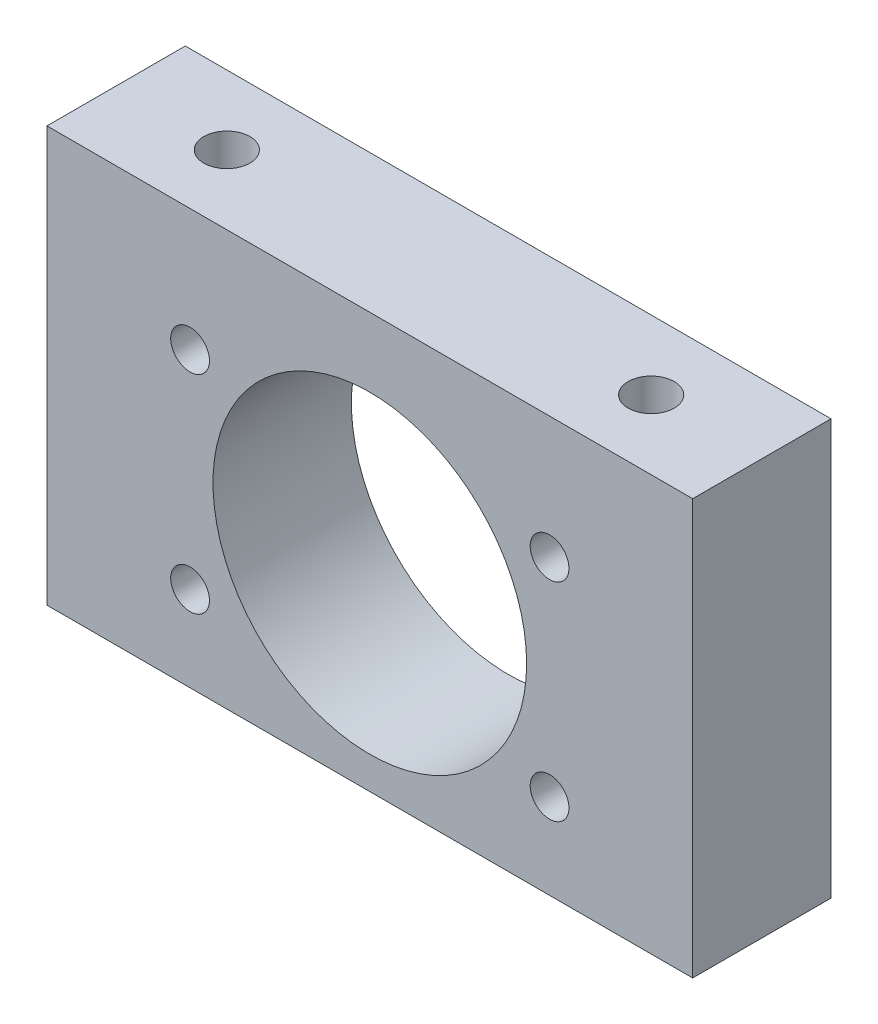
SolidWorks part; units mm, degrees
material "SKD11淬火HRC56-60"
ref_plane "前基準面" through (0, 0, 0) normal (0, 0, 1) x (1, 0, 0)
ref_plane "上基準面" through (0, 0, 0) normal (0, 1, 0) x (1, 0, 0)
ref_plane "右基準面" through (0, 0, 0) normal (1, 0, 0) x (0, 0, -1)
sketch "草图1" plane through (0, 0, 0) normal (0, 0, 1) x (1, 0, 0)
  line L1 (0, 0) -> (70, 0)
  line L2 (0, 0) -> (0, 45)
  line L3 (0, 45) -> (70, 45)
  line L4 (70, 0) -> (70, 45)
  dimension "D1" = 70
  dimension "D2" = 45
extrude "凸台-拉伸1" add sketch "草图1" along normal blind 15
sketch "草图2" plane through (0, 0, 15) normal (0, 0, 1) x (1, 0, 0)
  line L0 (35, 45) -> (35, 5.7798) construction
  line L1 (70, 45) -> (0, 45) construction
  circle A0 centre (35, 20.5) radius 17
  dimension "D1" = 34
  dimension "D2" = 24.5
extrude "切除-拉伸1" cut sketch "草图2" against normal through all
hole_wizard "M6 螺纹孔1" positions "草图4" profile "草图3" tap size "M6" standard "ISO"
sketch "草图4" plane through (0, 45, 0) normal (0, 1, 0) x (-1, 0, 0)
  line L0 (0, 7.5) -> (-70, 7.5) construction
  line L1 (0, 15) -> (0, 0) construction
  line L2 (-70, 15) -> (-70, 0) construction
  line L3 (-35, 0) -> (-35, 15) construction
  line L4 (-70, 0) -> (0, 0) construction
  line L5 (-70, 15) -> (0, 15) construction
  point P0 (-12, 7.5)
  point P1 (-58, 7.5)
  dimension "D1" = 46
sketch "草图3" plane through (12, 45, 7.5) normal (1, 0, 0) x (0, 0, 1)
  line L0 (0, 0) -> (0, 16.5022)
  line L1 (0, 16.5022) -> (2.5, 15)
  line L2 (2.5, 15) -> (2.5, 0)
  line L5 (2.5, 0) -> (0, 0)
  line L10 (0, 16.5022) -> (-2.5, 15) construction
  line L11 (0, -6.35) -> (0, 107.95) construction
  dimension "螺纹孔钻头直径" = 5
  dimension "螺纹孔钻头深度" = 15
  dimension "导头角度" = 118
cosmetic thread "孔螺蚊线1" parameters "D1"=12, "D2"=6
cosmetic thread "孔螺蚊线2" parameters "D1"=12, "D2"=6
hole_wizard "M5 螺纹孔1" positions "草图6" profile "草图5" tap size "M5" standard "ISO"
sketch "草图6" plane through (0, 0, 15) normal (0, 0, 1) x (1, 0, 0)
  point P0 (54.4856, 31.75)
  point P4 (15.5144, 31.75)
  point P7 (54.4856, 9.25)
  point P10 (15.5144, 9.25)
sketch "草图5" plane through (54.4856, 31.75, 15) normal (1, 0, 0) x (0, -1, 0)
  line L0 (0, 0) -> (0, 13.6618)
  line L1 (0, 13.6618) -> (2.1, 12.4)
  line L2 (2.1, 12.4) -> (2.1, 0)
  line L5 (2.1, 0) -> (0, 0)
  line L10 (0, 13.6618) -> (-2.1, 12.4) construction
  line L11 (0, -6.35) -> (0, 107.95) construction
  dimension "螺纹孔钻头直径" = 4.2
  dimension "螺纹孔钻头深度" = 12.4
  dimension "导头角度" = 118
cosmetic thread "孔螺蚊线3" parameters "D1"=10, "D2"=5
cosmetic thread "孔螺蚊线4" parameters "D1"=10, "D2"=5
cosmetic thread "孔螺蚊线5" parameters "D1"=10, "D2"=5
cosmetic thread "孔螺蚊线6" parameters "D1"=10, "D2"=5
